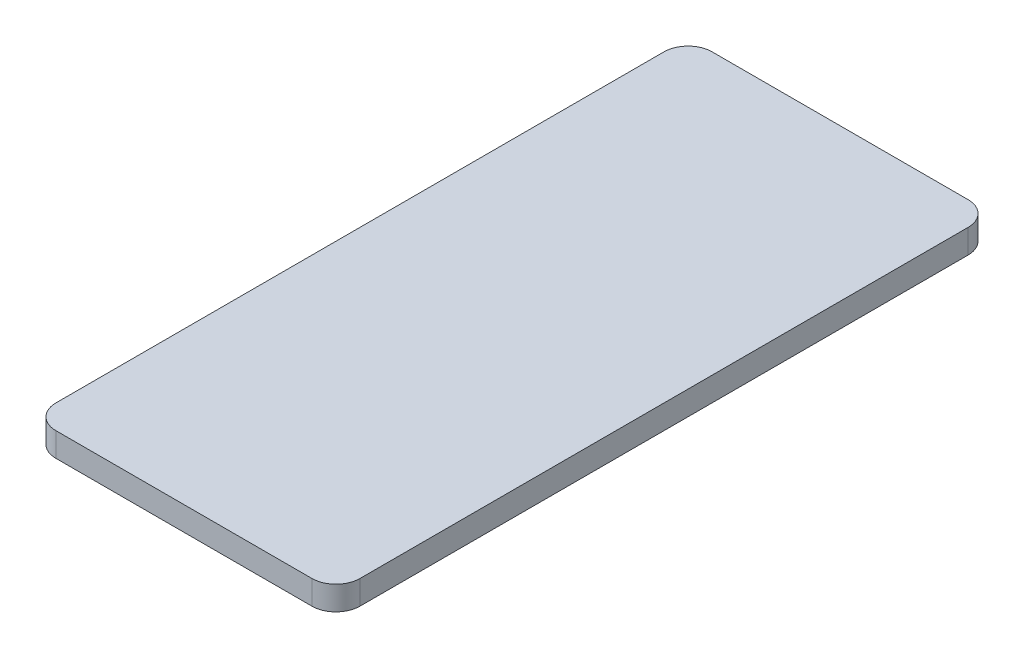
SolidWorks part; units mm, degrees
material "EN8"
ref_plane "Front Plane" through (0, 0, 0) normal (0, 0, 1) x (1, 0, 0)
ref_plane "Top Plane" through (0, 0, 0) normal (0, 1, 0) x (1, 0, 0)
ref_plane "Right Plane" through (0, 0, 0) normal (1, 0, 0) x (0, 0, -1)
sketch "Sketch1" plane through (0, 0, 0) normal (0, 1, 0) x (1, 0, 0)
  line L1 (-16, -41) -> (16, -41)
  line L2 (-19, -38) -> (-19, 38)
  line L3 (-16, 41) -> (16, 41)
  line L4 (19, -38) -> (19, 38)
  line L5 (-19, -41) -> (19, 41) construction
  line L6 (-19, 41) -> (19, -41) construction
  arc A0 (-16, -41) -> (-19, -38) centre (-16, -38) cw
  arc A1 (16, -41) -> (19, -38) centre (16, -38) ccw
  arc A2 (16, 41) -> (19, 38) centre (16, 38) cw
  arc A3 (-19, 38) -> (-16, 41) centre (-16, 38) cw
  point P0 (0, 0)
  dimension "D3" = 3
  dimension "D1" = 82
  dimension "D2" = 38
extrude "Boss-Extrude1" add sketch "Sketch1" along normal blind 3
